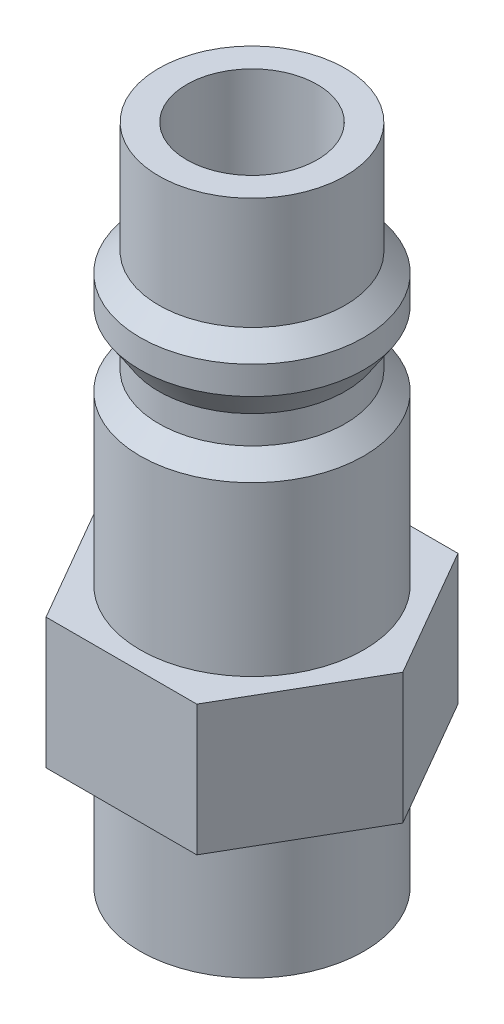
SolidWorks part; units mm, degrees
material "AISI 316 Gehärteter Edelstahlstab (SS)"
ref_plane "Ebene vorne" through (0, 0, 0) normal (0, 0, 1) x (1, 0, 0)
ref_plane "Ebene oben" through (0, 0, 0) normal (0, 1, 0) x (1, 0, 0)
ref_plane "Ebene rechts" through (0, 0, 0) normal (1, 0, 0) x (0, 0, -1)
sketch "Skizze1" plane through (0, 0, 0) normal (0, 1, 0) x (1, 0, 0)
  line L0 (-8.0829, 0) -> (8.0829, 0) construction
  line L1 (8.0829, 0) -> (4.0415, 7)
  line L2 (4.0415, 7) -> (-4.0415, 7)
  line L3 (-4.0415, 7) -> (-8.0829, 0)
  line L4 (-8.0829, 0) -> (-4.0415, -7)
  line L5 (-4.0415, -7) -> (4.0415, -7)
  line L6 (4.0415, -7) -> (8.0829, 0)
  circle A0 centre (0, 0) radius 7 construction
  point P11 (0, 0)
  dimension "D1" = 14
extrude "Aufsatz-Linear austragen1" add sketch "Skizze1" along normal blind 7
sketch "Skizze3" plane through (0, 0, 0) normal (0, 0, 1) x (1, 0, 0)
  line L0 (0, 0) -> (0, 50000) construction
  line L1 (0, 7) -> (-6, 7)
  line L2 (-4.0415, 7) -> (4.0415, 7) construction
  line L3 (-8.0829, 7) -> (-4.0415, 7) construction
  line L4 (-6, 7) -> (-6, 16)
  line L5 (-6, 16) -> (-5, 17)
  line L6 (-5, 17) -> (-5, 18.5)
  line L7 (-5, 18.5) -> (-6, 20)
  line L8 (-6, 20) -> (-6, 21.5)
  line L9 (-6, 21.5) -> (-5, 22.5)
  line L10 (-5, 22.5) -> (-5, 28.5)
  line L11 (-5, 28.5) -> (0, 28.5)
  line L12 (0, 28.5) -> (0, 7)
  line L13 (-6, 16) -> (0, 16) construction
  line L14 (-4.8927, 17) -> (0, 17) construction
  line L15 (-4.8927, 18.5) -> (0, 18.5) construction
  line L16 (-6, 20) -> (0, 20) construction
  line L17 (-6, 21.5) -> (0, 21.5) construction
  line L18 (-5, 22.5) -> (0, 22.5) construction
  point P17 (-5, 17.75)
  dimension "D1" = 10
  dimension "D2" = 12
  dimension "D3" = 10
  dimension "D4" = 12
  dimension "D5" = 1
  dimension "D6" = 6
  dimension "D7" = 9
  dimension "D8" = 1.5
  dimension "D9" = 1.5
  dimension "D10" = 1.5
revolve "Rotation1" add sketch "Skizze3" angle 360 about L0
sketch "Skizze4" plane through (0, 0, 0) normal (0, -1, 0) x (1, 0, 0)
  circle A0 centre (0, 0) radius 6
  dimension "D1" = 12
extrude "Aufsatz-Linear austragen3" add sketch "Skizze4" along normal blind 7
sketch "Skizze5" plane through (0, 28.5, 0) normal (0, 1, 0) x (1, 0, 0)
  circle A0 centre (0, 0) radius 3.5
  dimension "D1" = 7
extrude "Schnitt-Linear austragen1" cut sketch "Skizze5" against normal through all
